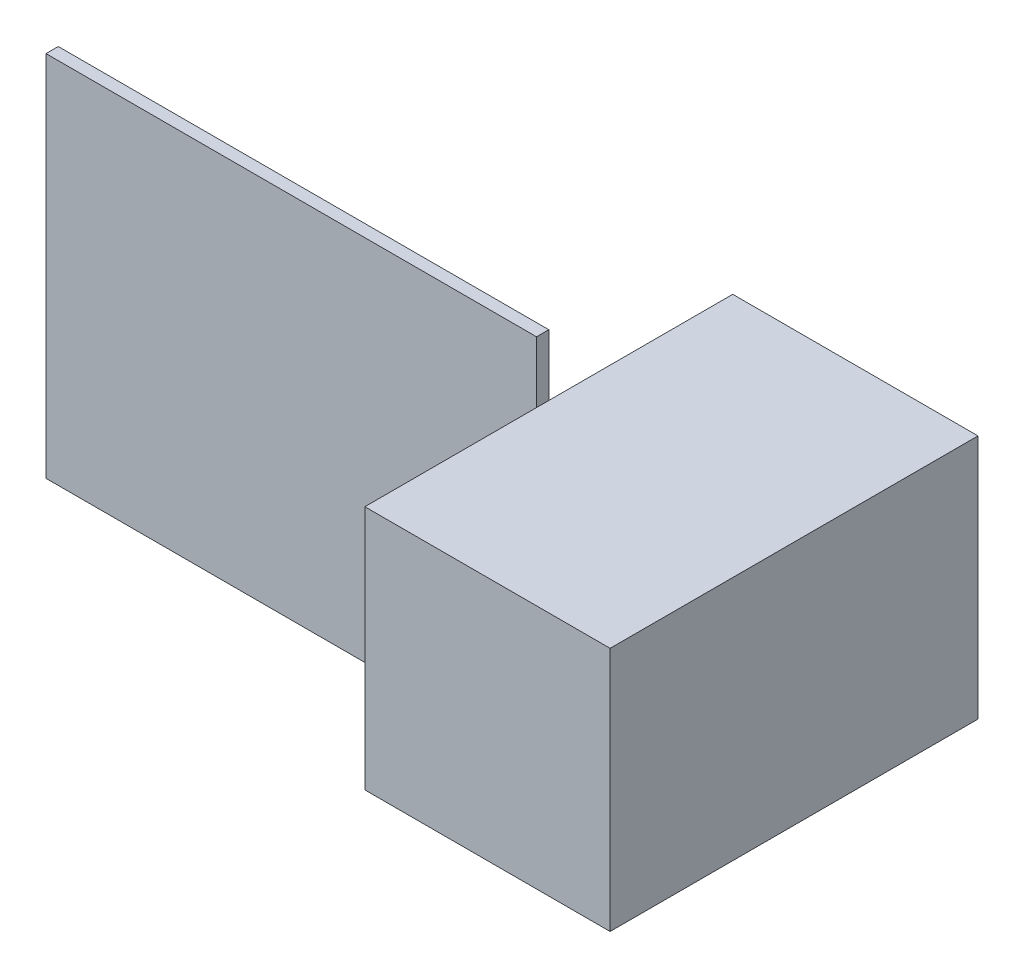
SolidWorks part; units mm, degrees
ref_plane "前视基准面" through (0, 0, 0) normal (0, 0, 1) x (1, 0, 0)
ref_plane "上视基准面" through (0, 0, 0) normal (0, 1, 0) x (1, 0, 0)
ref_plane "右视基准面" through (0, 0, 0) normal (1, 0, 0) x (0, 0, -1)
sketch "草图2" plane through (0, 0, 0) normal (0, 0, 1) x (1, 0, 0)
  line L1 (-40, 30) -> (40, 30)
  line L2 (-40, 30) -> (-40, -30)
  line L3 (-40, -30) -> (40, -30)
  line L4 (40, 30) -> (40, -30)
extrude "凸台-拉伸1" add sketch "草图2" along normal blind 2
sketch "草图3" plane through (40, 0, 0) normal (1, 0, 0) x (0, 0, -1)
  line L1 (-30, 20) -> (30, 20)
  line L2 (-30, 20) -> (-30, -20)
  line L3 (-30, -20) -> (30, -20)
  line L4 (30, 20) -> (30, -20)
extrude "凸台-拉伸2" add sketch "草图3" along normal blind 40
